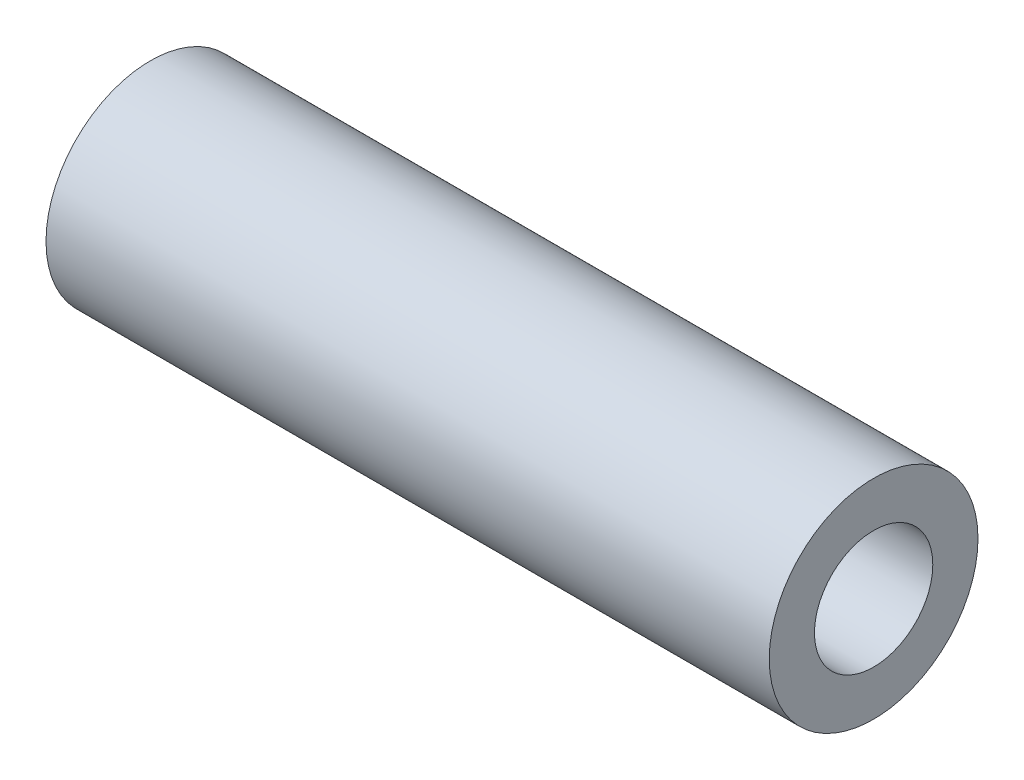
SolidWorks part; units mm, degrees
ref_plane "Front Plane" through (0, 0, 0) normal (0, 0, 1) x (1, 0, 0)
ref_plane "Top Plane" through (0, 0, 0) normal (0, 1, 0) x (1, 0, 0)
ref_plane "Right Plane" through (0, 0, 0) normal (1, 0, 0) x (0, 0, -1)
sketch "Sketch1" plane through (0, 0, 0) normal (1, 0, 0) x (0, 0, -1)
  circle A0 centre (0, 0) radius 1.8
  circle A1 centre (0, 0) radius 3.175
  dimension "D1" = 3.6
  dimension "D2" = 6.35
extrude "Boss-Extrude1" add sketch "Sketch1" along normal blind 22
